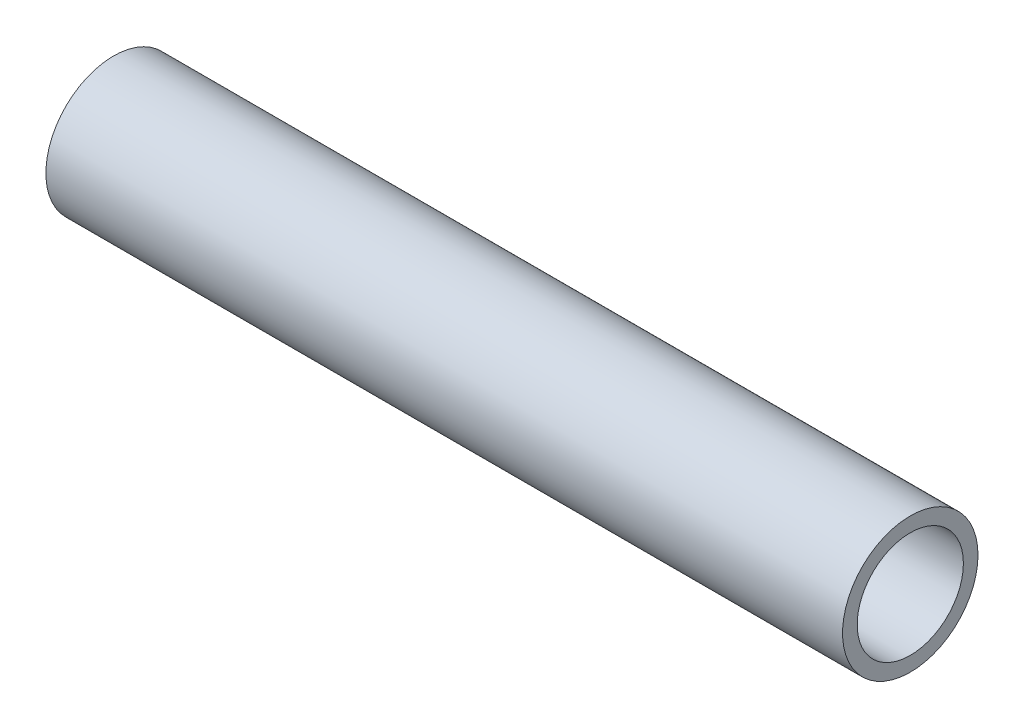
SolidWorks part; units mm, degrees
ref_plane "Front Plane" through (0, 0, 0) normal (0, 0, 1) x (1, 0, 0)
ref_plane "Top Plane" through (0, 0, 0) normal (0, 1, 0) x (1, 0, 0)
ref_plane "Right Plane" through (0, 0, 0) normal (1, 0, 0) x (0, 0, -1)
sketch "Sketch1" plane through (0, 0, 0) normal (1, 0, 0) x (0, 0, -1)
  circle A0 centre (0, 0) radius 4
  circle A1 centre (0, 0) radius 5.1
  dimension "D1" = 8
  dimension "D2" = 10.2
extrude "Boss-Extrude1" add sketch "Sketch1" along normal blind 60
